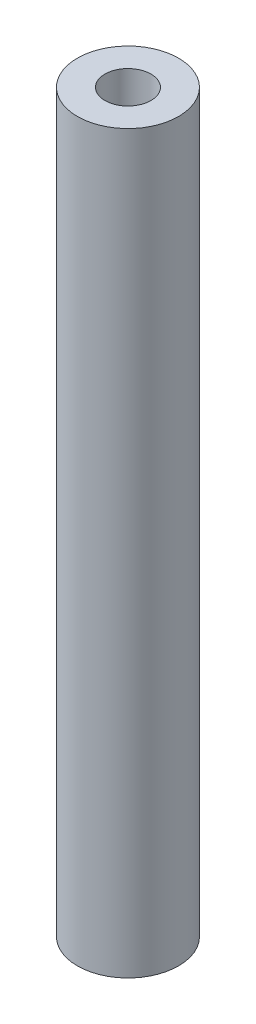
SolidWorks part; units mm, degrees
material "6061 合金"
ref_plane "前视基准面" through (0, 0, 0) normal (0, 0, 1) x (1, 0, 0)
ref_plane "上视基准面" through (0, 0, 0) normal (0, 1, 0) x (1, 0, 0)
ref_plane "右视基准面" through (0, 0, 0) normal (1, 0, 0) x (0, 0, -1)
other "Configuration Table"
sketch "草图1" plane through (0, 0, 0) normal (0, 1, 0) x (1, 0, 0)
  circle A0 centre (0, 0) radius 1.25
  circle A1 centre (0, 0) radius 2.75
  dimension "D1" = 5.5
  dimension "D2" = 2.5
extrude "凸台-拉伸1" add sketch "草图1" along normal blind 40
